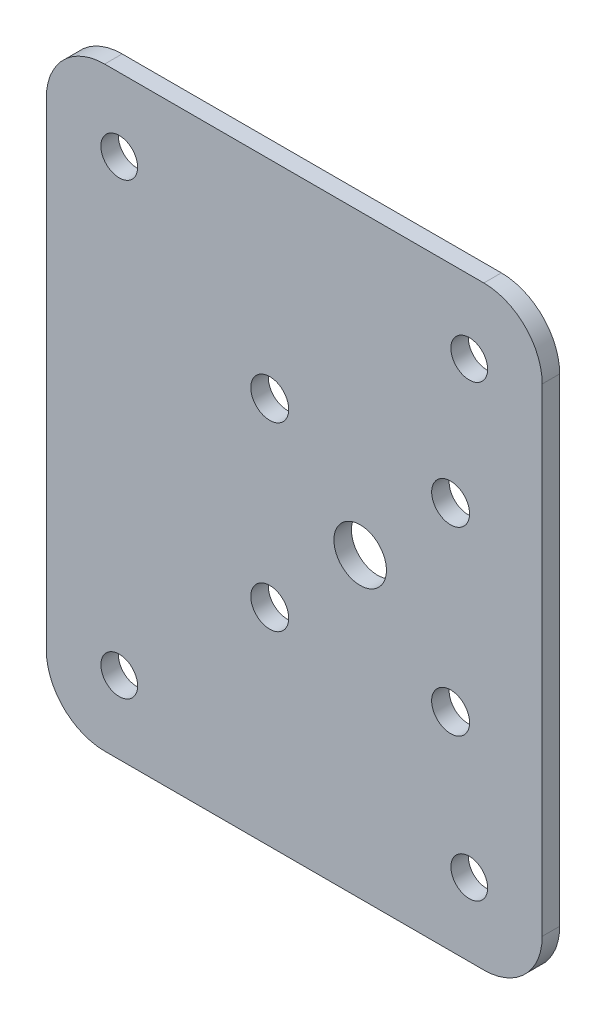
SolidWorks part; units mm, degrees
ref_plane "Front Plane" through (0, 0, 0) normal (0, 0, 1) x (1, 0, 0)
ref_plane "Top Plane" through (0, 0, 0) normal (0, 1, 0) x (1, 0, 0)
ref_plane "Right Plane" through (0, 0, 0) normal (1, 0, 0) x (0, 0, -1)
sketch "Croquis1" plane through (0, 0, 0) normal (0, 0, 1) x (1, 0, 0)
  line L0 (0, 0) -> (0, 8918.6876) construction
  line L1 (0, 0) -> (8918.6876, 0) construction
  line L3 (-53.8, 51) -> (31.2, 51)
  line L4 (-53.8, 51) -> (-53.8, -51)
  line L5 (-53.8, -51) -> (31.2, -51)
  line L6 (31.2, 51) -> (31.2, -51)
  circle A1 centre (0, 0) radius 4.5
  circle A2 centre (15.5, 15.5) radius 3.25
  circle A3 centre (-15.5, 15.5) radius 3.25
  circle A4 centre (15.5, -15.5) radius 3.25
  circle A5 centre (-15.5, -15.5) radius 3.25
  circle A6 centre (-41.3, 38.5) radius 3.15
  circle A7 centre (18.7, 38.5) radius 3.15
  circle A8 centre (18.7, -38.5) radius 3.15
  circle A9 centre (-41.3, -38.5) radius 3.15
  point P21 (31.2, 0)
  dimension "D1" = 9
  dimension "D2" = 6.5
  dimension "D3" = 15.5
  dimension "D4" = 15.5
  dimension "D8" = 6.3
  dimension "D9" = 12.5
  dimension "D10" = 12.5
  dimension "D11" = 6.3
  dimension "D12" = 12.5
  dimension "D13" = 12.5
  dimension "D5" = 85
  dimension "D6" = 102
  dimension "D7" = 53.8
extrude "Saliente-Extruir1" add sketch "Croquis1" along normal blind 3
fillet "Redondeo1" radius 10 4 edges at (-53.8, -51, 1.5) (-53.8, 51, 1.5) (31.2, -51, 1.5) (31.2, 51, 1.5)
